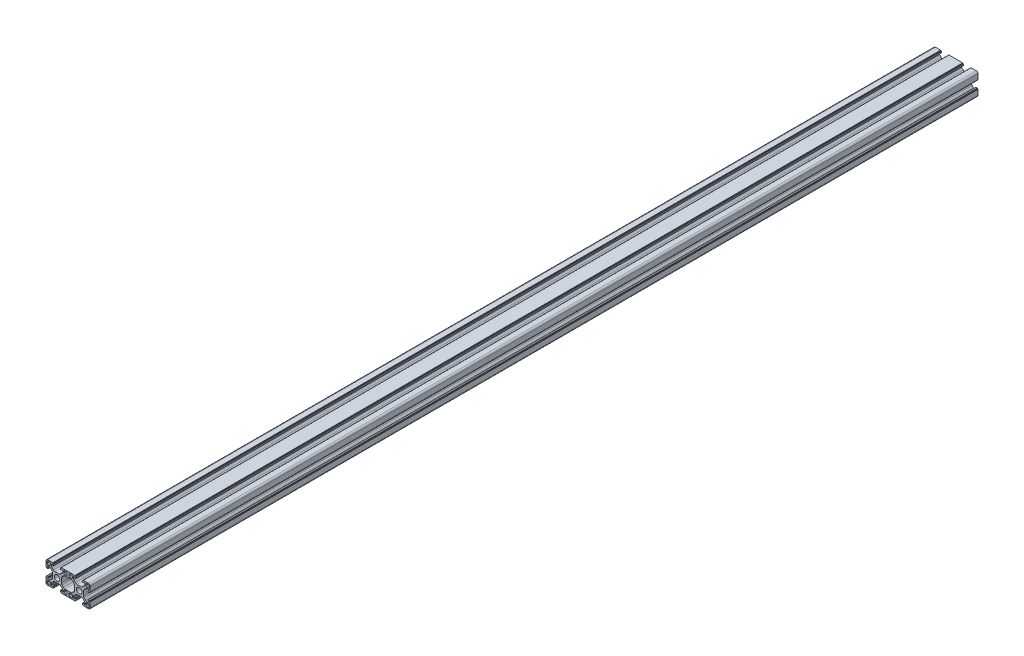
SolidWorks part; units mm, degrees
ref_plane "Спереди" through (0, 0, 0) normal (0, 0, 1) x (1, 0, 0)
ref_plane "Сверху" through (0, 0, 0) normal (0, 1, 0) x (1, 0, 0)
ref_plane "Справа" through (0, 0, 0) normal (1, 0, 0) x (0, 0, -1)
sketch "Эскиз1" plane through (0, 0, 0) normal (0, 0, 1) x (1, 0, 0)
  line L0 (-3.541, 7.6357) -> (-2.041, 6.1357) construction
  line L1 (17.959, 9.1357) -> (14.959, 6.1357) construction
  line L2 (-11.141, 0.0357) -> (-1.141, 10.0357) construction
  line L3 (8.859, 4.0357) -> (10.7578, 4.0357)
  line L4 (8.859, 0.0357) -> (18.859, 10.0357) construction
  line L5 (16.459, 7.6357) -> (14.959, 9.1357) construction
  line L6 (12.172, 4.6215) -> (13.4732, 5.9227)
  line L7 (15.759, 6.1357) -> (17.159, 6.1357)
  line L8 (14.959, 6.9357) -> (14.959, 8.3357)
  line L9 (17.159, 9.1357) -> (15.759, 9.1357)
  line L10 (14.059, 8.2357) -> (14.059, 7.3369)
  line L11 (12.6222, 8.1089) -> (13.1026, 8.5893)
  line L12 (12.059, 9.5848) -> (12.559, 9.5848)
  line L13 (12.4455, 8.0357) -> (12.159, 8.0357)
  line L14 (13.4561, 8.7357) -> (13.559, 8.7357)
  line L15 (12.559, 9.8857) -> (12.559, 9.5848)
  line L16 (11.909, 9.4348) -> (11.909, 8.2857)
  line L17 (17.359, 10.0357) -> (12.709, 10.0357)
  line L18 (17.959, 8.3357) -> (17.959, 6.9357)
  line L19 (18.859, 8.5357) -> (18.859, 3.8857)
  line L20 (18.2581, 3.0857) -> (17.109, 3.0857)
  line L21 (18.709, 3.7357) -> (18.4081, 3.7357)
  line L22 (17.559, 4.6328) -> (17.559, 4.7357)
  line L23 (16.859, 3.6221) -> (16.859, 3.3357)
  line L24 (18.4081, 3.2357) -> (18.4081, 3.7357)
  line L25 (16.9322, 3.7989) -> (17.4126, 4.2793)
  line L26 (17.059, 5.2357) -> (16.1602, 5.2357)
  line L27 (13.4448, 3.3487) -> (14.746, 4.6499)
  line L28 (12.859, 0.0357) -> (12.859, 1.9345)
  line L29 (12.859, 0.0357) -> (12.859, -1.8631)
  line L30 (13.4448, -3.2773) -> (14.746, -4.5785)
  line L31 (14.959, -6.8643) -> (14.959, -8.2643)
  line L32 (15.759, -6.0643) -> (17.159, -6.0643)
  line L33 (17.959, -8.2643) -> (17.959, -6.8643)
  line L34 (17.059, -5.1643) -> (16.1602, -5.1643)
  line L35 (16.9322, -3.7275) -> (17.4126, -4.2079)
  line L36 (18.4081, -3.1643) -> (18.4081, -3.6643)
  line L37 (16.859, -3.5507) -> (16.859, -3.2643)
  line L38 (17.559, -4.5614) -> (17.559, -4.6643)
  line L39 (18.709, -3.6643) -> (18.4081, -3.6643)
  line L40 (18.2581, -3.0143) -> (17.109, -3.0143)
  line L41 (18.859, -8.4643) -> (18.859, -3.8143)
  line L42 (17.159, -9.0643) -> (15.759, -9.0643)
  line L43 (17.359, -9.9643) -> (12.709, -9.9643)
  line L44 (11.909, -9.3634) -> (11.909, -8.2143)
  line L45 (12.559, -9.8143) -> (12.559, -9.5134)
  line L46 (13.4561, -8.6643) -> (13.559, -8.6643)
  line L47 (12.4455, -7.9643) -> (12.159, -7.9643)
  line L48 (12.059, -9.5134) -> (12.559, -9.5134)
  line L49 (12.6222, -8.0375) -> (13.1026, -8.5179)
  line L50 (14.059, -8.1643) -> (14.059, -7.2655)
  line L51 (12.172, -4.5501) -> (13.4732, -5.8513)
  line L52 (8.859, -3.9643) -> (10.7578, -3.9643)
  line L53 (17.959, -9.0643) -> (14.959, -6.0643) construction
  line L54 (8.859, 0.0357) -> (18.859, -9.9643) construction
  line L55 (16.459, -7.5643) -> (17.959, -6.0643) construction
  line L56 (8.859, -3.9643) -> (6.9602, -3.9643)
  line L57 (5.546, -4.5501) -> (4.2448, -5.8513)
  line L58 (1.959, -6.0643) -> (0.559, -6.0643)
  line L59 (2.759, -6.8643) -> (2.759, -8.2643)
  line L60 (0.559, -9.0643) -> (1.959, -9.0643)
  line L61 (3.659, -8.1643) -> (3.659, -7.2655)
  line L62 (5.0958, -8.0375) -> (4.6155, -8.5179)
  line L63 (5.659, -9.5134) -> (5.159, -9.5134)
  line L64 (5.2726, -7.9643) -> (5.559, -7.9643)
  line L65 (4.2619, -8.6643) -> (4.159, -8.6643)
  line L66 (5.159, -9.8143) -> (5.159, -9.5134)
  line L67 (5.809, -9.3634) -> (5.809, -8.2143)
  line L68 (0.359, -9.9643) -> (5.009, -9.9643)
  line L69 (-0.241, -8.2643) -> (-0.241, -6.8643)
  line L70 (0.659, -5.1643) -> (1.5578, -5.1643)
  line L71 (4.2732, -3.2773) -> (2.972, -4.5785)
  line L72 (4.859, 0.0357) -> (4.859, -1.8631)
  line L73 (-2.041, 9.1357) -> (-5.041, 6.1357) construction
  line L74 (-0.241, -9.0643) -> (2.759, -6.0643) construction
  line L75 (-3.541, -7.5643) -> (-5.041, -9.0643) construction
  line L76 (8.859, 0.0357) -> (-1.141, -9.9643) construction
  line L77 (1.259, -7.5643) -> (2.759, -9.0643) construction
  line L78 (4.859, 0.0357) -> (4.859, 1.9345)
  line L79 (4.2732, 3.3487) -> (2.972, 4.6499)
  line L80 (2.759, 6.9357) -> (2.759, 8.3357)
  line L81 (1.959, 6.1357) -> (0.559, 6.1357)
  line L82 (-0.241, 8.3357) -> (-0.241, 6.9357)
  line L83 (0.659, 5.2357) -> (1.5578, 5.2357)
  line L84 (0.559, 9.1357) -> (1.959, 9.1357)
  line L85 (0.359, 10.0357) -> (5.009, 10.0357)
  line L86 (5.809, 9.4348) -> (5.809, 8.2857)
  line L87 (5.159, 9.8857) -> (5.159, 9.5848)
  line L88 (4.2619, 8.7357) -> (4.159, 8.7357)
  line L89 (5.2726, 8.0357) -> (5.559, 8.0357)
  line L90 (5.659, 9.5848) -> (5.159, 9.5848)
  line L91 (5.0958, 8.1089) -> (4.6155, 8.5893)
  line L92 (3.659, 8.2357) -> (3.659, 7.3369)
  line L93 (5.546, 4.6215) -> (4.2448, 5.9227)
  line L94 (8.859, 4.0357) -> (6.9602, 4.0357)
  line L95 (-2.905, 0.0357) -> (20.3634, 0.0357) construction
  line L96 (-0.241, 9.1357) -> (2.759, 6.1357) construction
  line L97 (8.859, -12.0507) -> (8.859, 10.7546) construction
  line L98 (8.859, 0.0357) -> (-1.141, 10.0357) construction
  line L99 (1.259, 7.6357) -> (-0.241, 6.1357) construction
  line L100 (-11.141, 0.0357) -> (-1.141, -9.9643) construction
  line L101 (-2.041, -9.0643) -> (-5.041, -6.0643) construction
  line L102 (-18.741, -7.5643) -> (-20.241, -6.0643) construction
  line L103 (-11.141, 0.0357) -> (-21.141, -9.9643) construction
  line L104 (-20.241, -9.0643) -> (-17.241, -6.0643) construction
  line L105 (-18.741, 7.6357) -> (-17.241, 9.1357) construction
  line L106 (-11.141, 0.0357) -> (-21.141, 10.0357) construction
  line L107 (-20.241, 9.1357) -> (-17.241, 6.1357) construction
  line L108 (-11.141, 4.0357) -> (-9.2422, 4.0357)
  line L109 (-7.828, 4.6215) -> (-6.5268, 5.9227)
  line L110 (-5.941, 8.2357) -> (-5.941, 7.3369)
  line L111 (-7.3778, 8.1089) -> (-6.8974, 8.5893)
  line L112 (-7.941, 9.5848) -> (-7.441, 9.5848)
  line L113 (-7.5545, 8.0357) -> (-7.841, 8.0357)
  line L114 (-6.5439, 8.7357) -> (-6.441, 8.7357)
  line L115 (-7.441, 9.8857) -> (-7.441, 9.5848)
  line L116 (-8.091, 9.4348) -> (-8.091, 8.2857)
  line L117 (-2.641, 10.0357) -> (-7.291, 10.0357)
  line L118 (-2.841, 9.1357) -> (-4.241, 9.1357)
  line L119 (-2.941, 5.2357) -> (-3.8398, 5.2357)
  line L120 (-2.041, 8.3357) -> (-2.041, 6.9357)
  line L121 (-4.241, 6.1357) -> (-2.841, 6.1357)
  line L122 (-5.041, 6.9357) -> (-5.041, 8.3357)
  line L123 (-6.5552, 3.3487) -> (-5.254, 4.6499)
  line L124 (-7.141, 0.0357) -> (-7.141, 1.9345)
  line L125 (-7.141, 0.0357) -> (-7.141, -1.8631)
  line L126 (-6.5552, -3.2773) -> (-5.254, -4.5785)
  line L127 (-2.941, -5.1643) -> (-3.8398, -5.1643)
  line L128 (-2.041, -8.2643) -> (-2.041, -6.8643)
  line L129 (-2.641, -9.9643) -> (-7.291, -9.9643)
  line L130 (-8.091, -9.3634) -> (-8.091, -8.2143)
  line L131 (-7.441, -9.8143) -> (-7.441, -9.5134)
  line L132 (-6.5439, -8.6643) -> (-6.441, -8.6643)
  line L133 (-7.5545, -7.9643) -> (-7.841, -7.9643)
  line L134 (-7.941, -9.5134) -> (-7.441, -9.5134)
  line L135 (-7.3778, -8.0375) -> (-6.8974, -8.5179)
  line L136 (-5.941, -8.1643) -> (-5.941, -7.2655)
  line L137 (-2.841, -9.0643) -> (-4.241, -9.0643)
  line L138 (-5.041, -6.8643) -> (-5.041, -8.2643)
  line L139 (-4.241, -6.0643) -> (-2.841, -6.0643)
  line L140 (-7.828, -4.5501) -> (-6.5268, -5.8513)
  line L141 (-11.141, -3.9643) -> (-9.2422, -3.9643)
  line L142 (-11.141, -3.9643) -> (-13.0398, -3.9643)
  line L143 (-14.454, -4.5501) -> (-15.7552, -5.8513)
  line L144 (-16.341, -8.1643) -> (-16.341, -7.2655)
  line L145 (-14.9042, -8.0375) -> (-15.3845, -8.5179)
  line L146 (-14.341, -9.5134) -> (-14.841, -9.5134)
  line L147 (-14.7274, -7.9643) -> (-14.441, -7.9643)
  line L148 (-15.7381, -8.6643) -> (-15.841, -8.6643)
  line L149 (-14.841, -9.8143) -> (-14.841, -9.5134)
  line L150 (-14.191, -9.3634) -> (-14.191, -8.2143)
  line L151 (-19.641, -9.9643) -> (-14.991, -9.9643)
  line L152 (-19.441, -9.0643) -> (-18.041, -9.0643)
  line L153 (-21.141, -8.4643) -> (-21.141, -3.8143)
  line L154 (-20.5401, -3.0143) -> (-19.391, -3.0143)
  line L155 (-20.991, -3.6643) -> (-20.6901, -3.6643)
  line L156 (-19.841, -4.5614) -> (-19.841, -4.6643)
  line L157 (-19.141, -3.5507) -> (-19.141, -3.2643)
  line L158 (-20.6901, -3.1643) -> (-20.6901, -3.6643)
  line L159 (-19.2142, -3.7275) -> (-19.6945, -4.2079)
  line L160 (-19.341, -5.1643) -> (-18.4422, -5.1643)
  line L161 (-20.241, -8.2643) -> (-20.241, -6.8643)
  line L162 (-18.041, -6.0643) -> (-19.441, -6.0643)
  line L163 (-17.241, -6.8643) -> (-17.241, -8.2643)
  line L164 (-15.7268, -3.2773) -> (-17.028, -4.5785)
  line L165 (-15.141, 0.0357) -> (-15.141, -1.8631)
  line L166 (-15.141, 0.0357) -> (-15.141, 1.9345)
  line L167 (-15.7268, 3.3487) -> (-17.028, 4.6499)
  line L168 (-19.341, 5.2357) -> (-18.4422, 5.2357)
  line L169 (-19.2142, 3.7989) -> (-19.6945, 4.2793)
  line L170 (-20.6901, 3.2357) -> (-20.6901, 3.7357)
  line L171 (-19.141, 3.6221) -> (-19.141, 3.3357)
  line L172 (-19.841, 4.6328) -> (-19.841, 4.7357)
  line L173 (-20.991, 3.7357) -> (-20.6901, 3.7357)
  line L174 (-20.5401, 3.0857) -> (-19.391, 3.0857)
  line L175 (-21.141, 8.5357) -> (-21.141, 3.8857)
  line L176 (-20.241, 8.3357) -> (-20.241, 6.9357)
  line L177 (-19.641, 10.0357) -> (-14.991, 10.0357)
  line L178 (-14.191, 9.4348) -> (-14.191, 8.2857)
  line L179 (-14.841, 9.8857) -> (-14.841, 9.5848)
  line L180 (-15.7381, 8.7357) -> (-15.841, 8.7357)
  line L181 (-14.7274, 8.0357) -> (-14.441, 8.0357)
  line L182 (-14.341, 9.5848) -> (-14.841, 9.5848)
  line L183 (-14.9042, 8.1089) -> (-15.3845, 8.5893)
  line L184 (-16.341, 8.2357) -> (-16.341, 7.3369)
  line L185 (-19.441, 9.1357) -> (-18.041, 9.1357)
  line L186 (-17.241, 6.9357) -> (-17.241, 8.3357)
  line L187 (-18.041, 6.1357) -> (-19.441, 6.1357)
  line L188 (-14.454, 4.6215) -> (-15.7552, 5.9227)
  line L189 (-11.141, 4.0357) -> (-13.0398, 4.0357)
  line L190 (-2.641, -9.9643) -> (0.359, -9.9643)
  line L191 (-2.941, -5.1643) -> (0.659, -5.1643)
  line L192 (-2.941, 5.2357) -> (0.659, 5.2357)
  line L193 (-2.641, 10.0357) -> (0.359, 10.0357)
  arc A0 (17.959, 8.3357) -> (17.159, 9.1357) centre (17.159, 8.3357) ccw
  arc A1 (15.759, 9.1357) -> (14.959, 8.3357) centre (15.759, 8.3357) ccw
  arc A2 (15.759, 6.1357) -> (14.959, 6.9357) centre (15.759, 6.9357) cw
  arc A3 (17.359, 10.0357) -> (18.859, 8.5357) centre (17.359, 8.5357) cw
  arc A4 (12.059, 9.5848) -> (11.909, 9.4348) centre (12.059, 9.4348) ccw
  arc A5 (12.709, 10.0357) -> (12.559, 9.8857) centre (12.709, 9.8857) ccw
  arc A6 (12.4455, 8.0357) -> (12.6222, 8.1089) centre (12.4455, 8.2857) ccw
  arc A7 (12.159, 8.0357) -> (11.909, 8.2857) centre (12.159, 8.2857) cw
  arc A8 (13.1026, 8.5893) -> (13.4561, 8.7357) centre (13.4561, 8.2357) cw
  arc A9 (13.559, 8.7357) -> (14.059, 8.2357) centre (13.559, 8.2357) cw
  arc A10 (11.359, 0.0357) -> (8.859, 2.5357) centre (8.859, 0.0357) ccw
  arc A11 (10.7578, 4.0357) -> (12.172, 4.6215) centre (10.7578, 6.0357) ccw
  arc A12 (14.059, 7.3369) -> (13.4732, 5.9227) centre (12.059, 7.3369) cw
  arc A13 (17.959, 6.9357) -> (17.159, 6.1357) centre (17.159, 6.9357) cw
  arc A14 (17.559, 4.7357) -> (17.059, 5.2357) centre (17.059, 4.7357) ccw
  arc A15 (17.4126, 4.2793) -> (17.559, 4.6328) centre (17.059, 4.6328) ccw
  arc A16 (16.859, 3.3357) -> (17.109, 3.0857) centre (17.109, 3.3357) ccw
  arc A17 (16.859, 3.6221) -> (16.9322, 3.7989) centre (17.109, 3.6221) cw
  arc A18 (18.859, 3.8857) -> (18.709, 3.7357) centre (18.709, 3.8857) cw
  arc A19 (18.4081, 3.2357) -> (18.2581, 3.0857) centre (18.2581, 3.2357) cw
  arc A20 (16.1602, 5.2357) -> (14.746, 4.6499) centre (16.1602, 3.2357) ccw
  arc A21 (12.859, 1.9345) -> (13.4448, 3.3487) centre (14.859, 1.9345) cw
  arc A22 (17.159, -9.0643) -> (17.959, -8.2643) centre (17.159, -8.2643) ccw
  arc A23 (17.959, -6.8643) -> (17.159, -6.0643) centre (17.159, -6.8643) ccw
  arc A24 (14.959, -6.8643) -> (15.759, -6.0643) centre (15.759, -6.8643) cw
  arc A25 (18.859, -8.4643) -> (17.359, -9.9643) centre (17.359, -8.4643) cw
  arc A26 (18.4081, -3.1643) -> (18.2581, -3.0143) centre (18.2581, -3.1643) ccw
  arc A27 (18.859, -3.8143) -> (18.709, -3.6643) centre (18.709, -3.8143) ccw
  arc A28 (16.859, -3.5507) -> (16.9322, -3.7275) centre (17.109, -3.5507) ccw
  arc A29 (16.859, -3.2643) -> (17.109, -3.0143) centre (17.109, -3.2643) cw
  arc A30 (17.4126, -4.2079) -> (17.559, -4.5614) centre (17.059, -4.5614) cw
  arc A31 (17.559, -4.6643) -> (17.059, -5.1643) centre (17.059, -4.6643) cw
  arc A32 (8.859, -2.4643) -> (11.359, 0.0357) centre (8.859, 0.0357) ccw
  arc A33 (12.859, -1.8631) -> (13.4448, -3.2773) centre (14.859, -1.8631) ccw
  arc A34 (16.1602, -5.1643) -> (14.746, -4.5785) centre (16.1602, -3.1643) cw
  arc A35 (15.759, -9.0643) -> (14.959, -8.2643) centre (15.759, -8.2643) cw
  arc A36 (13.559, -8.6643) -> (14.059, -8.1643) centre (13.559, -8.1643) ccw
  arc A37 (13.1026, -8.5179) -> (13.4561, -8.6643) centre (13.4561, -8.1643) ccw
  arc A38 (12.159, -7.9643) -> (11.909, -8.2143) centre (12.159, -8.2143) ccw
  arc A39 (12.4455, -7.9643) -> (12.6222, -8.0375) centre (12.4455, -8.2143) cw
  arc A40 (12.709, -9.9643) -> (12.559, -9.8143) centre (12.709, -9.8143) cw
  arc A41 (12.059, -9.5134) -> (11.909, -9.3634) centre (12.059, -9.3634) cw
  arc A42 (14.059, -7.2655) -> (13.4732, -5.8513) centre (12.059, -7.2655) ccw
  arc A43 (10.7578, -3.9643) -> (12.172, -4.5501) centre (10.7578, -5.9643) cw
  arc A44 (-0.241, -8.2643) -> (0.559, -9.0643) centre (0.559, -8.2643) ccw
  arc A45 (1.959, -9.0643) -> (2.759, -8.2643) centre (1.959, -8.2643) ccw
  arc A46 (1.959, -6.0643) -> (2.759, -6.8643) centre (1.959, -6.8643) cw
  arc A47 (5.659, -9.5134) -> (5.809, -9.3634) centre (5.659, -9.3634) ccw
  arc A48 (5.009, -9.9643) -> (5.159, -9.8143) centre (5.009, -9.8143) ccw
  arc A49 (5.2726, -7.9643) -> (5.0958, -8.0375) centre (5.2726, -8.2143) ccw
  arc A50 (5.559, -7.9643) -> (5.809, -8.2143) centre (5.559, -8.2143) cw
  arc A51 (4.6155, -8.5179) -> (4.2619, -8.6643) centre (4.2619, -8.1643) cw
  arc A52 (4.159, -8.6643) -> (3.659, -8.1643) centre (4.159, -8.1643) cw
  arc A53 (6.359, 0.0357) -> (8.859, -2.4643) centre (8.859, 0.0357) ccw
  arc A54 (6.9602, -3.9643) -> (5.546, -4.5501) centre (6.9602, -5.9643) ccw
  arc A55 (3.659, -7.2655) -> (4.2448, -5.8513) centre (5.659, -7.2655) cw
  arc A56 (-0.241, -6.8643) -> (0.559, -6.0643) centre (0.559, -6.8643) cw
  arc A57 (1.5578, -5.1643) -> (2.972, -4.5785) centre (1.5578, -3.1643) ccw
  arc A58 (4.859, -1.8631) -> (4.2732, -3.2773) centre (2.859, -1.8631) cw
  arc A59 (0.559, 9.1357) -> (-0.241, 8.3357) centre (0.559, 8.3357) ccw
  arc A60 (-0.241, 6.9357) -> (0.559, 6.1357) centre (0.559, 6.9357) ccw
  arc A61 (2.759, 6.9357) -> (1.959, 6.1357) centre (1.959, 6.9357) cw
  arc A62 (8.859, 2.5357) -> (6.359, 0.0357) centre (8.859, 0.0357) ccw
  arc A63 (4.859, 1.9345) -> (4.2732, 3.3487) centre (2.859, 1.9345) ccw
  arc A64 (1.5578, 5.2357) -> (2.972, 4.6499) centre (1.5578, 3.2357) cw
  arc A65 (1.959, 9.1357) -> (2.759, 8.3357) centre (1.959, 8.3357) cw
  arc A66 (4.159, 8.7357) -> (3.659, 8.2357) centre (4.159, 8.2357) ccw
  arc A67 (4.6155, 8.5893) -> (4.2619, 8.7357) centre (4.2619, 8.2357) ccw
  arc A68 (5.559, 8.0357) -> (5.809, 8.2857) centre (5.559, 8.2857) ccw
  arc A69 (5.2726, 8.0357) -> (5.0958, 8.1089) centre (5.2726, 8.2857) cw
  arc A70 (5.009, 10.0357) -> (5.159, 9.8857) centre (5.009, 9.8857) cw
  arc A71 (5.659, 9.5848) -> (5.809, 9.4348) centre (5.659, 9.4348) cw
  arc A72 (3.659, 7.3369) -> (4.2448, 5.9227) centre (5.659, 7.3369) ccw
  arc A73 (6.9602, 4.0357) -> (5.546, 4.6215) centre (6.9602, 6.0357) cw
  arc A74 (-9.2422, 4.0357) -> (-7.828, 4.6215) centre (-9.2422, 6.0357) ccw
  arc A75 (-5.941, 7.3369) -> (-6.5268, 5.9227) centre (-7.941, 7.3369) cw
  arc A76 (-7.941, 9.5848) -> (-8.091, 9.4348) centre (-7.941, 9.4348) ccw
  arc A77 (-7.291, 10.0357) -> (-7.441, 9.8857) centre (-7.291, 9.8857) ccw
  arc A78 (-7.5545, 8.0357) -> (-7.3778, 8.1089) centre (-7.5545, 8.2857) ccw
  arc A79 (-7.841, 8.0357) -> (-8.091, 8.2857) centre (-7.841, 8.2857) cw
  arc A80 (-6.8974, 8.5893) -> (-6.5439, 8.7357) centre (-6.5439, 8.2357) cw
  arc A81 (-6.441, 8.7357) -> (-5.941, 8.2357) centre (-6.441, 8.2357) cw
  arc A82 (-4.241, 9.1357) -> (-5.041, 8.3357) centre (-4.241, 8.3357) ccw
  arc A83 (-3.8398, 5.2357) -> (-5.254, 4.6499) centre (-3.8398, 3.2357) ccw
  arc A84 (-7.141, 1.9345) -> (-6.5552, 3.3487) centre (-5.141, 1.9345) cw
  arc A85 (-11.141, 2.5357) -> (-8.641, 0.0357) centre (-11.141, 0.0357) cw
  arc A86 (-5.041, 6.9357) -> (-4.241, 6.1357) centre (-4.241, 6.9357) ccw
  arc A87 (-2.041, 6.9357) -> (-2.841, 6.1357) centre (-2.841, 6.9357) cw
  arc A88 (-2.841, 9.1357) -> (-2.041, 8.3357) centre (-2.841, 8.3357) cw
  arc A89 (-7.141, -1.8631) -> (-6.5552, -3.2773) centre (-5.141, -1.8631) ccw
  arc A90 (-3.8398, -5.1643) -> (-5.254, -4.5785) centre (-3.8398, -3.1643) cw
  arc A91 (-2.041, -6.8643) -> (-2.841, -6.0643) centre (-2.841, -6.8643) ccw
  arc A92 (-5.941, -7.2655) -> (-6.5268, -5.8513) centre (-7.941, -7.2655) ccw
  arc A93 (-9.2422, -3.9643) -> (-7.828, -4.5501) centre (-9.2422, -5.9643) cw
  arc A94 (-8.641, 0.0357) -> (-11.141, -2.4643) centre (-11.141, 0.0357) cw
  arc A95 (-6.441, -8.6643) -> (-5.941, -8.1643) centre (-6.441, -8.1643) ccw
  arc A96 (-6.8974, -8.5179) -> (-6.5439, -8.6643) centre (-6.5439, -8.1643) ccw
  arc A97 (-7.841, -7.9643) -> (-8.091, -8.2143) centre (-7.841, -8.2143) ccw
  arc A98 (-7.5545, -7.9643) -> (-7.3778, -8.0375) centre (-7.5545, -8.2143) cw
  arc A99 (-7.291, -9.9643) -> (-7.441, -9.8143) centre (-7.291, -9.8143) cw
  arc A100 (-7.941, -9.5134) -> (-8.091, -9.3634) centre (-7.941, -9.3634) cw
  arc A101 (-4.241, -6.0643) -> (-5.041, -6.8643) centre (-4.241, -6.8643) ccw
  arc A102 (-4.241, -9.0643) -> (-5.041, -8.2643) centre (-4.241, -8.2643) cw
  arc A103 (-2.041, -8.2643) -> (-2.841, -9.0643) centre (-2.841, -8.2643) cw
  arc A104 (-13.0398, -3.9643) -> (-14.454, -4.5501) centre (-13.0398, -5.9643) ccw
  arc A105 (-16.341, -7.2655) -> (-15.7552, -5.8513) centre (-14.341, -7.2655) cw
  arc A106 (-14.341, -9.5134) -> (-14.191, -9.3634) centre (-14.341, -9.3634) ccw
  arc A107 (-14.991, -9.9643) -> (-14.841, -9.8143) centre (-14.991, -9.8143) ccw
  arc A108 (-14.7274, -7.9643) -> (-14.9042, -8.0375) centre (-14.7274, -8.2143) ccw
  arc A109 (-14.441, -7.9643) -> (-14.191, -8.2143) centre (-14.441, -8.2143) cw
  arc A110 (-15.3845, -8.5179) -> (-15.7381, -8.6643) centre (-15.7381, -8.1643) cw
  arc A111 (-15.841, -8.6643) -> (-16.341, -8.1643) centre (-15.841, -8.1643) cw
  arc A112 (-18.041, -9.0643) -> (-17.241, -8.2643) centre (-18.041, -8.2643) ccw
  arc A113 (-18.4422, -5.1643) -> (-17.028, -4.5785) centre (-18.4422, -3.1643) ccw
  arc A114 (-15.141, -1.8631) -> (-15.7268, -3.2773) centre (-17.141, -1.8631) cw
  arc A115 (-11.141, -2.4643) -> (-13.641, 0.0357) centre (-11.141, 0.0357) cw
  arc A116 (-19.841, -4.6643) -> (-19.341, -5.1643) centre (-19.341, -4.6643) ccw
  arc A117 (-19.6945, -4.2079) -> (-19.841, -4.5614) centre (-19.341, -4.5614) ccw
  arc A118 (-19.141, -3.2643) -> (-19.391, -3.0143) centre (-19.391, -3.2643) ccw
  arc A119 (-19.141, -3.5507) -> (-19.2142, -3.7275) centre (-19.391, -3.5507) cw
  arc A120 (-21.141, -3.8143) -> (-20.991, -3.6643) centre (-20.991, -3.8143) cw
  arc A121 (-20.6901, -3.1643) -> (-20.5401, -3.0143) centre (-20.5401, -3.1643) cw
  arc A122 (-21.141, -8.4643) -> (-19.641, -9.9643) centre (-19.641, -8.4643) ccw
  arc A123 (-17.241, -6.8643) -> (-18.041, -6.0643) centre (-18.041, -6.8643) ccw
  arc A124 (-20.241, -6.8643) -> (-19.441, -6.0643) centre (-19.441, -6.8643) cw
  arc A125 (-19.441, -9.0643) -> (-20.241, -8.2643) centre (-19.441, -8.2643) cw
  arc A126 (-15.141, 1.9345) -> (-15.7268, 3.3487) centre (-17.141, 1.9345) ccw
  arc A127 (-18.4422, 5.2357) -> (-17.028, 4.6499) centre (-18.4422, 3.2357) cw
  arc A128 (-20.6901, 3.2357) -> (-20.5401, 3.0857) centre (-20.5401, 3.2357) ccw
  arc A129 (-21.141, 3.8857) -> (-20.991, 3.7357) centre (-20.991, 3.8857) ccw
  arc A130 (-19.141, 3.6221) -> (-19.2142, 3.7989) centre (-19.391, 3.6221) ccw
  arc A131 (-19.141, 3.3357) -> (-19.391, 3.0857) centre (-19.391, 3.3357) cw
  arc A132 (-19.6945, 4.2793) -> (-19.841, 4.6328) centre (-19.341, 4.6328) cw
  arc A133 (-19.841, 4.7357) -> (-19.341, 5.2357) centre (-19.341, 4.7357) cw
  arc A134 (-20.241, 6.9357) -> (-19.441, 6.1357) centre (-19.441, 6.9357) ccw
  arc A135 (-16.341, 7.3369) -> (-15.7552, 5.9227) centre (-14.341, 7.3369) ccw
  arc A136 (-13.0398, 4.0357) -> (-14.454, 4.6215) centre (-13.0398, 6.0357) cw
  arc A137 (-13.641, 0.0357) -> (-11.141, 2.5357) centre (-11.141, 0.0357) cw
  arc A138 (-15.841, 8.7357) -> (-16.341, 8.2357) centre (-15.841, 8.2357) ccw
  arc A139 (-15.3845, 8.5893) -> (-15.7381, 8.7357) centre (-15.7381, 8.2357) ccw
  arc A140 (-14.441, 8.0357) -> (-14.191, 8.2857) centre (-14.441, 8.2857) ccw
  arc A141 (-14.7274, 8.0357) -> (-14.9042, 8.1089) centre (-14.7274, 8.2857) cw
  arc A142 (-14.991, 10.0357) -> (-14.841, 9.8857) centre (-14.991, 9.8857) cw
  arc A143 (-14.341, 9.5848) -> (-14.191, 9.4348) centre (-14.341, 9.4348) cw
  arc A144 (-19.641, 10.0357) -> (-21.141, 8.5357) centre (-19.641, 8.5357) ccw
  arc A145 (-18.041, 6.1357) -> (-17.241, 6.9357) centre (-18.041, 6.9357) ccw
  arc A146 (-18.041, 9.1357) -> (-17.241, 8.3357) centre (-18.041, 8.3357) cw
  arc A147 (-20.241, 8.3357) -> (-19.441, 9.1357) centre (-19.441, 8.3357) cw
  point P0 (8.859, 0.0357)
  point P12 (8.859, 0.0357)
  point P45 (17.559, 3.7357)
  point P104 (12.559, -8.6643)
  point P155 (12.559, 8.7357)
  point P163 (17.559, -3.6643)
  point P164 (8.859, -3.8886)
  point P166 (8.859, 0.0357)
  point P224 (5.159, -8.6643)
  point P225 (4.9347, 0.0357)
  point P227 (8.859, 0.0357)
  point P267 (5.159, 8.7357)
  point P272 (12.7833, 0.0357)
  point P288 (8.859, 3.96)
  point P290 (8.859, 0.0357)
  point P515 (-11.141, 3.96)
  point P516 (-15.0653, 0.0357)
  point P517 (-7.441, 8.7357)
  point P518 (-7.2167, 0.0357)
  point P519 (-7.441, -8.6643)
  point P520 (-11.141, -3.8886)
  point P521 (-19.841, -3.6643)
  point P522 (-14.841, 8.7357)
  point P523 (-14.841, -8.6643)
  point P524 (-19.841, 3.7357)
  dimension "D3" = 5
  dimension "D6" = 2
  dimension "D1" = 2
  dimension "D2" = 6
  dimension "D4" = 4
  dimension "D5" = 0.9
extrude "Бобышка-Вытянуть1" add sketch "Эскиз1" along normal blind 804
